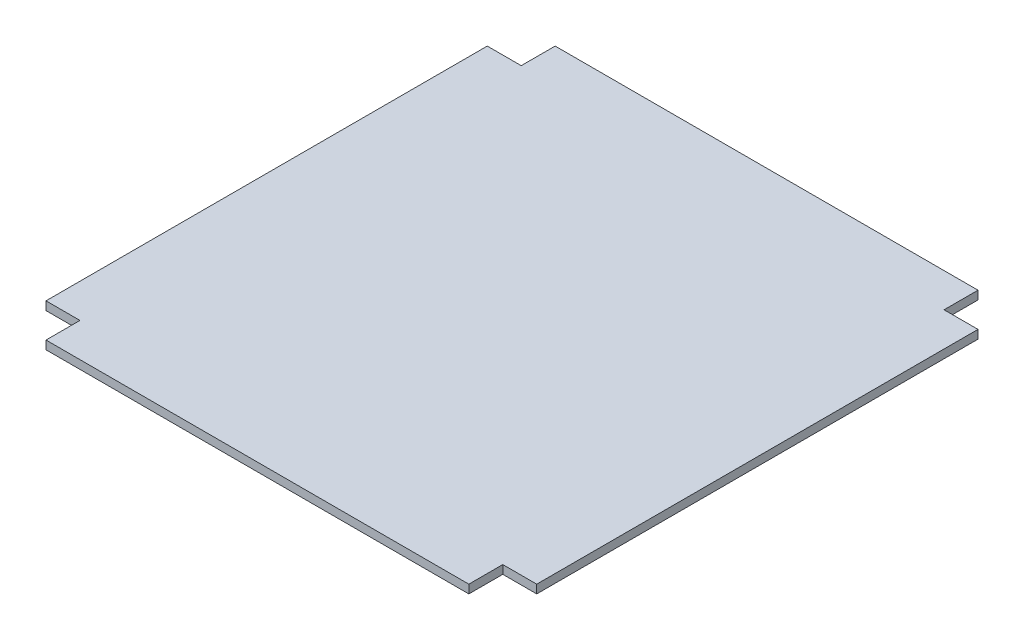
SolidWorks part; units mm, degrees
ref_plane "Plan de face" through (0, 0, 0) normal (0, 0, 1) x (1, 0, 0)
ref_plane "Plan de dessus" through (0, 0, 0) normal (0, 1, 0) x (1, 0, 0)
ref_plane "Plan de droite" through (0, 0, 0) normal (1, 0, 0) x (0, 0, -1)
sketch "Esquisse1" plane through (0, 0, 0) normal (0, 1, 0) x (1, 0, 0)
  line L0 (-174.5839, 0) -> (222.3951, 0) construction
  line L1 (-144.5683, 40) -> (-104.5683, 40)
  line L2 (-104.5683, 40) -> (-104.5683, -40)
  line L3 (-144.5683, -40) -> (-104.5683, -40)
  line L4 (0, 143.2846) -> (0, -128.3979) construction
  line L5 (144.5683, -40) -> (104.5683, -40)
  line L6 (104.5683, 40) -> (104.5683, -40)
  line L7 (144.5683, 40) -> (104.5683, 40)
  line L8 (-144.5683, 40) -> (-144.5683, 150)
  line L9 (-144.5683, 150) -> (144.5683, 150)
  line L10 (144.5683, 150) -> (144.5683, 40)
  line L11 (144.5683, -40) -> (144.5683, -150)
  line L12 (144.5683, -150) -> (-144.5683, -150)
  line L13 (-144.5683, -150) -> (-144.5683, -40)
  line L14 (-144.5683, 130) -> (-124.5683, 130)
  line L15 (-124.5683, 130) -> (-124.5683, 150)
  line L16 (144.5683, 130) -> (124.5683, 130)
  line L17 (124.5683, 130) -> (124.5683, 150)
  line L18 (124.5683, -130) -> (124.5683, -150)
  line L19 (144.5683, -130) -> (124.5683, -130)
  line L20 (-124.5683, -130) -> (-124.5683, -150)
  line L21 (-144.5683, -130) -> (-124.5683, -130)
  line L22 (-144.5683, -40) -> (-144.5683, 40)
  line L23 (144.5683, 40) -> (144.5683, -40)
  circle A0 centre (0, 0) radius 150
  point P9 (-104.5683, 0)
  dimension "D1" = 300
  dimension "D2" = 40
  dimension "D3" = 40
  dimension "D10" = 20
  dimension "D11" = 20
extrude "Boss.-Extru.1" add sketch "Esquisse1" along normal blind 5
